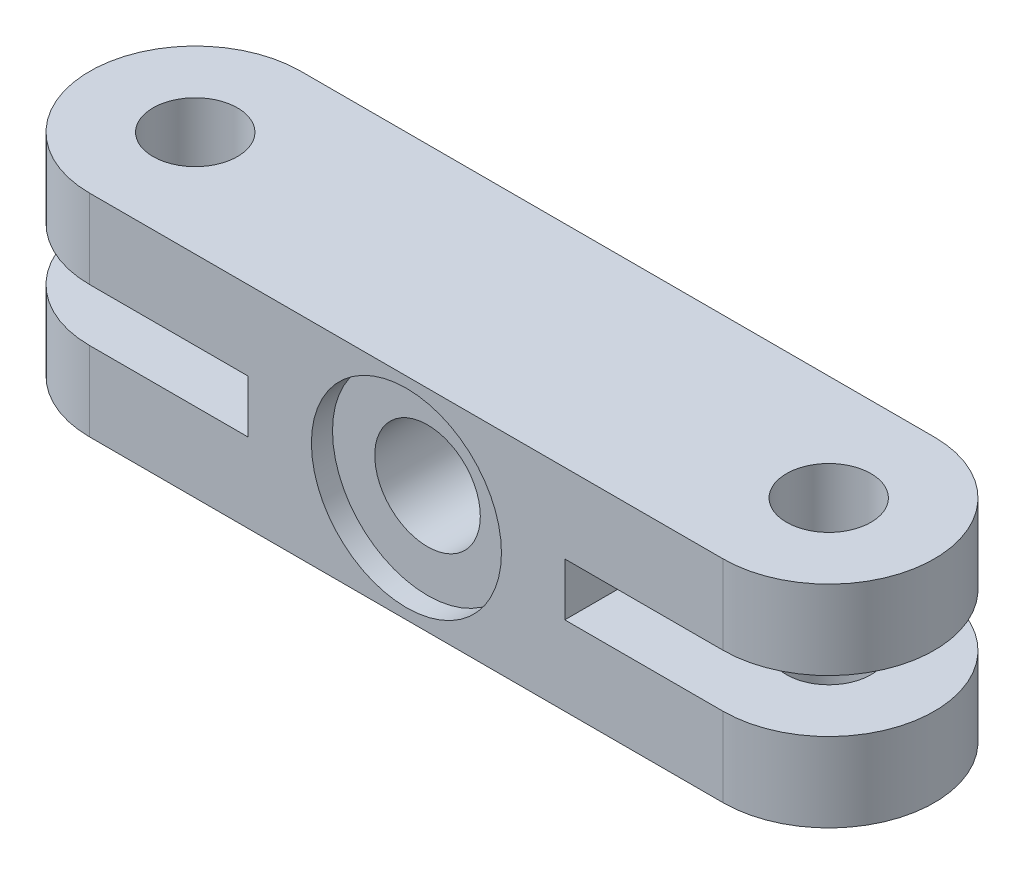
SolidWorks part; units mm, degrees
ref_plane "前视基准面" through (0, 0, 0) normal (0, 0, 1) x (1, 0, 0)
ref_plane "上视基准面" through (0, 0, 0) normal (0, 1, 0) x (1, 0, 0)
ref_plane "右视基准面" through (0, 0, 0) normal (1, 0, 0) x (0, 0, -1)
sketch "草图1" plane through (0, 0, 0) normal (0, 1, 0) x (1, 0, 0)
  line L0 (-30, 0) -> (30, 0) construction
  line L1 (-30, 10) -> (30, 10)
  line L2 (-30, -10) -> (30, -10)
  arc A0 (-30, 10) -> (-30, -10) centre (-30, 0) ccw
  arc A1 (30, -10) -> (30, 10) centre (30, 0) ccw
  circle A2 centre (-30, 0) radius 4
  circle A3 centre (30, 0) radius 4
  point P2 (0, 0)
  point P12 (0, 0)
  dimension "D2" = 10
  dimension "D3" = 8
  dimension "D4" = 8
  dimension "D1" = 60
extrude "凸台-拉伸1" add sketch "草图1" along normal mid plane 20
sketch "草图2" plane through (0, 0, 10) normal (0, 0, 1) x (1, 0, 0)
  line L0 (0, 10) -> (0, -10.7155) construction
  line L1 (-30, 10) -> (30, 10) construction
  line L2 (40, -10) -> (40, 10) construction
  line L3 (15, 2.5) -> (40, 2.5)
  line L4 (15, 2.5) -> (15, -2.5)
  line L5 (15, -2.5) -> (40, -2.5)
  line L6 (40, 2.5) -> (40, -2.5)
  line L7 (15, 2.5) -> (40, -2.5) construction
  line L8 (15, -2.5) -> (40, 2.5) construction
  line L9 (-15, 2.5) -> (-40, 2.5)
  line L10 (-15, 2.5) -> (-15, -2.5)
  line L11 (-15, -2.5) -> (-40, -2.5)
  line L12 (-40, 2.5) -> (-40, -2.5)
  point P5 (27.5, 0)
  dimension "D1" = 25
  dimension "D2" = 5
extrude "切除-拉伸1" cut sketch "草图2" against normal through all
hole_wizard "孔1" positions "草图3" profile "草图4" legacy
sketch "草图3" plane through (0, 0, 10) normal (0, 0, 1) x (1, 0, 0)
  point P0 (0, 0)
sketch "草图4" plane through (0, 0, 10) normal (1, 0, 0) x (0, -1, 0)
  line L0 (0, 0) -> (0, 20)
  line L1 (0, 20) -> (5, 20)
  line L2 (5, 20) -> (5, 2)
  line L3 (5, 2) -> (9, 2)
  line L4 (9, 2) -> (9, 0)
  line L5 (9, 0) -> (0, 0)
  line L6 (0, 110) -> (0, -10) construction
  dimension "直径" = 10
  dimension "深度" = 20
  dimension "柱坑直径" = 18
  dimension "柱坑深度" = 2
